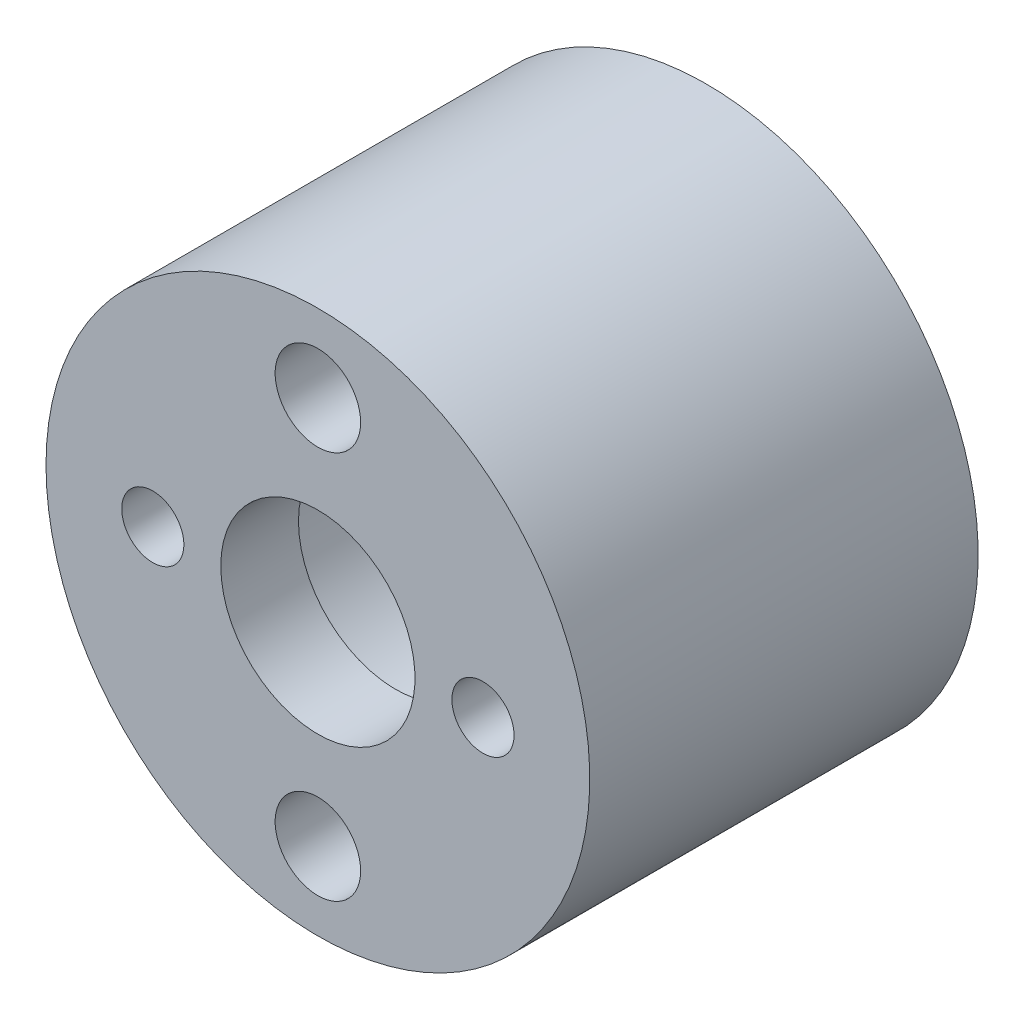
SolidWorks part; units mm, degrees
ref_plane "Front Plane" through (0, 0, 0) normal (0, 0, 1) x (1, 0, 0)
ref_plane "Top Plane" through (0, 0, 0) normal (0, 1, 0) x (1, 0, 0)
ref_plane "Right Plane" through (0, 0, 0) normal (1, 0, 0) x (0, 0, -1)
sketch "Sketch1" plane through (0, 0, 0) normal (0, 1, 0) x (1, 0, 0)
  line L0 (0, 0) -> (7, 0)
  line L1 (7, 10) -> (3.5, 10)
  line L2 (3.5, 10) -> (3.5, 2)
  line L3 (3.5, 2) -> (0, 2)
  line L4 (0, 2) -> (0, 0)
  line L5 (7, 0) -> (7, 10)
  dimension "D1" = 3.5
  dimension "D2" = 8
  dimension "D3" = 7
  dimension "D4" = 2
revolve "Revolve1" add sketch "Sketch1" angle 360 about L4
sketch "Sketch2" plane through (0, 0, -2) normal (0, 0, -1) x (-1, 0, 0)
  circle A0 centre (0, 0) radius 2.5
  dimension "D1" = 5
extrude "Cut-Extrude1" cut sketch "Sketch2" against normal through all contours A0
sketch "Sketch3" plane through (0, 0, 0) normal (0, 0, 1) x (1, 0, 0)
  circle A0 centre (0, 5) radius 1.1
  circle A1 centre (0, -5) radius 1.1
  circle A2 centre (4.25, 0) radius 0.8
  circle A3 centre (-4.25, 0) radius 0.8
  dimension "D1" = 2.2
  dimension "D2" = 2.2
  dimension "D3" = 1.6
  dimension "D4" = 1.6
  dimension "D5" = 4.25
  dimension "D6" = 4.25
  dimension "D7" = 5
  dimension "D8" = 5
extrude "Cut-Extrude2" cut sketch "Sketch3" against normal up to surface (2 mm away) up to face at (-2.5, 0, -2)
chamfer "Chamfer1" distance 0.3 angle 45 1 edges at (-3.5, 0, -10)
